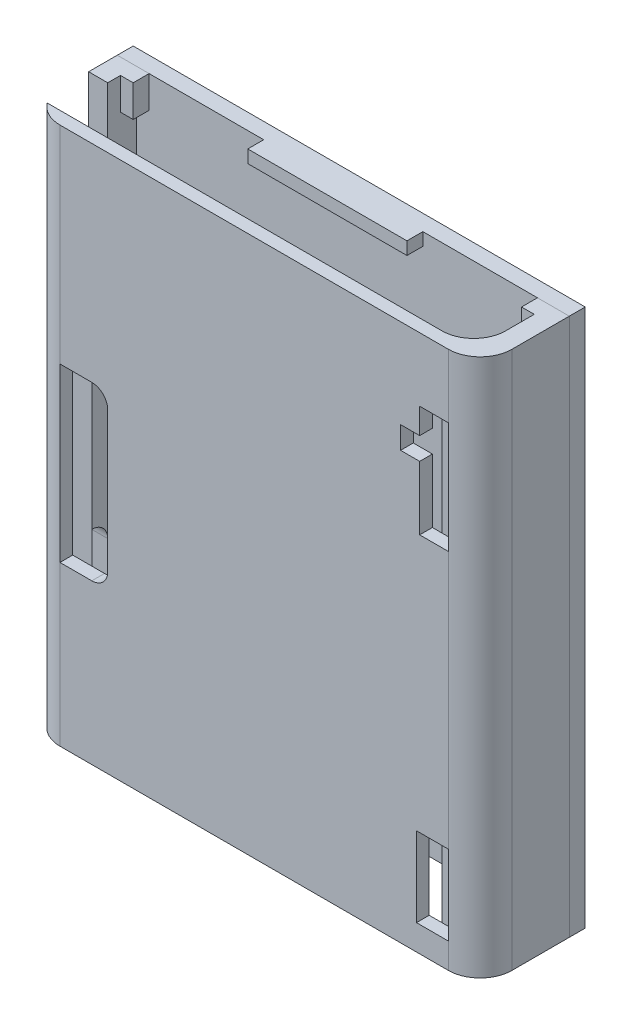
SolidWorks part; units mm, degrees
material "PEI"
ref_plane "前视基准面" through (0, 0, 0) normal (0, 0, 1) x (1, 0, 0)
ref_plane "上视基准面" through (0, 0, 0) normal (0, 1, 0) x (1, 0, 0)
ref_plane "右视基准面" through (0, 0, 0) normal (1, 0, 0) x (0, 0, -1)
other "Configuration Table"
sketch "草图2" plane through (0, 0, 0) normal (0, 0, 1) x (1, 0, 0)
  line L1 (-38.7902, 28.5822) -> (91.2098, 28.5822)
  line L2 (-38.7902, 28.5822) -> (-38.7902, -140.4178)
  line L3 (-38.7902, -140.4178) -> (91.2098, -140.4178)
  line L4 (91.2098, 28.5822) -> (91.2098, -140.4178)
  dimension "D1" = 130
  dimension "D2" = 169
extrude "凸台-拉伸1" add sketch "草图2" along normal blind 5
sketch "草图3" plane through (0, 0, 5) normal (0, 0, 1) x (1, 0, 0)
  line L0 (91.2098, 28.5822) -> (-38.7902, 28.5822) construction
  line L1 (1.2098, 24.5822) -> (51.2098, 24.5822)
  line L2 (-34.7902, -11.4178) -> (-34.7902, -100.4178)
  line L3 (1.2098, -136.4178) -> (51.2098, -136.4178)
  line L4 (87.2098, -11.4178) -> (87.2098, -100.4178)
  line L5 (-38.7902, -140.4178) -> (91.2098, -140.4178) construction
  line L6 (-38.7902, 28.5822) -> (-38.7902, -140.4178) construction
  line L7 (91.2098, -140.4178) -> (91.2098, 28.5822) construction
  line L8 (1.2098, 28.5822) -> (1.2098, 24.5822)
  line L9 (51.2098, -140.4178) -> (51.2098, -136.4178)
  line L10 (-38.7902, -11.4178) -> (-34.7902, -11.4178)
  line L11 (-38.7902, -100.4178) -> (-34.7902, -100.4178)
  line L12 (-38.7902, 28.5822) -> (-38.7902, -140.4178)
  line L13 (-38.7902, -140.4178) -> (91.2098, -140.4178)
  line L14 (91.2098, -140.4178) -> (91.2098, 28.5822)
  line L15 (91.2098, 28.5822) -> (-38.7902, 28.5822)
  line L16 (-38.7902, -11.4178) -> (-38.7902, -100.4178)
  line L17 (1.2098, -140.4178) -> (51.2098, -140.4178)
  line L18 (91.2098, -100.4178) -> (91.2098, -11.4178)
  line L19 (51.2098, 28.5822) -> (1.2098, 28.5822)
  line L20 (1.2098, -136.4178) -> (1.2098, -140.4178)
  line L21 (87.2098, -11.4178) -> (91.2098, -11.4178)
  line L22 (51.2098, 24.5822) -> (51.2098, 28.5822)
  line L23 (87.2098, -100.4178) -> (91.2098, -100.4178)
  dimension "D1" = 4
  dimension "D2" = 4
  dimension "D3" = 4
  dimension "D4" = 4
  dimension "D6" = 40
  dimension "D7" = 40
  dimension "D8" = 40
  dimension "D9" = 40
  dimension "D5" = 0
extrude "凸台-拉伸2" add sketch "草图3" along normal blind 5
sketch "草图4" plane through (0, -11.4178, 0) normal (0, 1, 0) x (1, 0, 0)
  line L0 (91.2098, -10) -> (91.2098, -12)
  line L1 (91.2098, -12) -> (86.2098, -12)
  line L2 (86.2098, -12) -> (85.2098, -10)
  line L3 (85.2098, -10) -> (87.2098, -10)
  line L4 (87.2098, -10) -> (87.2098, -5) construction
  line L5 (91.2098, -10) -> (87.2098, -10) construction
  line M6 (87.2098, -10) -> (91.2098, -10)
  dimension "D1" = 2
  dimension "D2" = 2
  dimension "D3" = 5
extrude "凸台-拉伸3" add sketch "草图4" against normal up to surface (89 mm away) contours L3 L2 L1 L0 M6 up to face at (89.2098, -100.4178, 7.5)
sketch "草图5" plane through (0, 0, 5) normal (0, 0, 1) x (1, 0, 0)
  line L0 (-38.7902, -140.4178) -> (1.2098, -140.4178) construction
  line L1 (-38.7902, 28.5822) -> (-44.7902, 28.5822)
  line L2 (-38.7902, 28.5822) -> (-38.7902, -140.4178)
  line L3 (-38.7902, -140.4178) -> (-44.7902, -140.4178)
  line L4 (-44.7902, 28.5822) -> (-44.7902, -140.4178)
  line L5 (91.2098, 28.5822) -> (97.2098, 28.5822)
  line L6 (91.2098, 28.5822) -> (91.2098, -140.4178)
  line L7 (91.2098, -140.4178) -> (97.2098, -140.4178)
  line L8 (97.2098, 28.5822) -> (97.2098, -140.4178)
  line L9 (51.2098, -140.4178) -> (91.2098, -140.4178) construction
  dimension "D1" = 6
  dimension "D2" = 6
extrude "凸台-拉伸4" add sketch "草图5" against normal up to surface (5 mm away) up to face at (26.2098, -55.9178, 0)
sketch "草图6" plane through (0, 28.5822, 0) normal (0, 1, 0) x (1, 0, 0)
  line L0 (-38.7902, -10) -> (-38.7902, -5) construction
  line L1 (-44.7902, -5) -> (-38.7902, -5)
  line L2 (-44.7902, -5) -> (-44.7902, -23)
  line L4 (-38.7902, -5) -> (-38.7902, -19)
  line L5 (-34.7902, -33) -> (87.2098, -33)
  line L6 (-38.7902, -33) -> (-38.7902, -32.1652)
  line L7 (-28.7902, -29) -> (81.2098, -29)
  line L10 (97.2098, -23) -> (97.2098, -5)
  line L11 (97.2098, -5) -> (91.2098, -5)
  line L12 (91.2098, -19) -> (91.2098, -5)
  line L13 (97.2098, 0) -> (97.2098, -5) construction
  line L14 (1.2098, -5) -> (-44.7902, -5) construction
  arc A0 (97.2098, -23) -> (87.2098, -33) centre (87.2098, -23) cw
  arc A1 (81.2098, -29) -> (91.2098, -19) centre (81.2098, -19) ccw
  arc A2 (-34.7902, -33) -> (-44.7902, -23) centre (-34.7902, -23) cw
  arc A3 (-28.7902, -29) -> (-38.7902, -19) centre (-28.7902, -19) cw
  line M7 (-44.7902, -5) -> (1.2098, -5)
  line M11 (51.2098, -5) -> (97.2098, -5)
  dimension "D3" = 10
  dimension "D1" = 24
  dimension "D2" = 4
extrude "凸台-拉伸5" add sketch "草图6" against normal up to surface (169 mm away) separate body contours L7 A3 L4 L2 A2 L5 A0 L10 L12 A1 M7 M11 up to face at (26.2098, -140.4178, 5)
sketch "草图7" plane through (0, 0, 5) normal (0, 0, 1) x (1, 0, 0)
  line L0 (-34.7902, -100.4178) -> (-34.7902, -11.4178) construction
  line L1 (91.2098, -140.4178) -> (87.2098, -140.4178)
  line L2 (91.2098, -140.4178) -> (91.2098, -130.4178)
  line L3 (91.2098, -130.4178) -> (87.2098, -130.4178)
  line L4 (87.2098, -140.4178) -> (87.2098, -130.4178)
  line L5 (-38.7902, -140.4178) -> (-34.7902, -140.4178)
  line L6 (-38.7902, -140.4178) -> (-38.7902, -130.4178)
  line L7 (-38.7902, -130.4178) -> (-34.7902, -130.4178)
  line L8 (-34.7902, -140.4178) -> (-34.7902, -130.4178)
  line L9 (91.2098, 28.5822) -> (87.2098, 28.5822)
  line L10 (91.2098, 28.5822) -> (91.2098, 18.5822)
  line L11 (91.2098, 18.5822) -> (87.2098, 18.5822)
  line L12 (87.2098, 28.5822) -> (87.2098, 18.5822)
  line L13 (-38.7902, 28.5822) -> (-34.7902, 28.5822)
  line L14 (-38.7902, 28.5822) -> (-38.7902, 18.5822)
  line L15 (-38.7902, 18.5822) -> (-34.7902, 18.5822)
  line L16 (-34.7902, 28.5822) -> (-34.7902, 18.5822)
  line L17 (87.2098, -11.4178) -> (87.2098, -100.4178) construction
  line M6 (-44.7902, -140.4178) -> (1.2098, -140.4178)
  line M12 (97.2098, 28.5822) -> (51.2098, 28.5822)
  line M16 (1.2098, 28.5822) -> (-44.7902, 28.5822)
  dimension "D1" = 10
  dimension "D2" = 10
  dimension "D3" = 10
  dimension "D4" = 10
extrude "凸台-拉伸6" add sketch "草图7" along normal up to surface (5 mm away) contours L8 L7 L6 M6 | L16 L14 L15 M16 | L12 L11 L10 M12 | L4 L3 L2 L1 up to face at (-36.7902, -55.9178, 10)
sketch "草图8" plane through (0, 0, 0) normal (0, 0, -1) x (-1, 0, 0)
  line L1 (-97.2098, 28.5822) -> (-87.2098, 28.5822)
  line L2 (-97.2098, 28.5822) -> (-97.2098, 18.5822)
  line L3 (-97.2098, 18.5822) -> (-87.2098, 18.5822)
  line L4 (-87.2098, 28.5822) -> (-87.2098, 18.5822)
  line L5 (-97.2098, 28.5822) -> (-87.2098, 18.5822) construction
  line L6 (-97.2098, 18.5822) -> (-87.2098, 28.5822) construction
  line L7 (44.7902, 28.5822) -> (34.7902, 28.5822)
  line L8 (44.7902, 28.5822) -> (44.7902, 18.5822)
  line L9 (44.7902, 18.5822) -> (34.7902, 18.5822)
  line L10 (34.7902, 28.5822) -> (34.7902, 18.5822)
  line L11 (44.7902, 28.5822) -> (34.7902, 18.5822) construction
  line L12 (44.7902, 18.5822) -> (34.7902, 28.5822) construction
  line L13 (44.7902, -140.4178) -> (34.7902, -140.4178)
  line L14 (44.7902, -140.4178) -> (44.7902, -130.4178)
  line L15 (44.7902, -130.4178) -> (34.7902, -130.4178)
  line L16 (34.7902, -140.4178) -> (34.7902, -130.4178)
  line L17 (44.7902, -140.4178) -> (34.7902, -130.4178) construction
  line L18 (44.7902, -130.4178) -> (34.7902, -140.4178) construction
  line L19 (-97.2098, -140.4178) -> (-87.2098, -140.4178)
  line L20 (-97.2098, -140.4178) -> (-97.2098, -130.4178)
  line L21 (-97.2098, -130.4178) -> (-87.2098, -130.4178)
  line L22 (-87.2098, -140.4178) -> (-87.2098, -130.4178)
  line L23 (-97.2098, -140.4178) -> (-87.2098, -130.4178) construction
  line L24 (-97.2098, -130.4178) -> (-87.2098, -140.4178) construction
  circle A0 centre (-92.2098, 23.5822) radius 2.2
  circle A1 centre (39.7902, 23.5822) radius 2.2
  circle A2 centre (-92.2098, -135.4178) radius 2.2
  circle A3 centre (39.7902, -135.4178) radius 2.2
  point P4 (-92.2098, 23.5822)
  point P10 (39.7902, 23.5822)
  point P16 (39.7902, -135.4178)
  point P22 (-92.2098, -135.4178)
  dimension "D4" = 4.4
  dimension "D5" = 4.4
  dimension "D6" = 4.4
  dimension "D7" = 4.4
  dimension "D1" = 10
  dimension "D2" = 10
  dimension "D3" = 10
extrude "切除-拉伸1" cut sketch "草图8" against normal blind 9 contours A3 | A1 | A0 | A2
sketch "草图9" plane through (-44.7902, 0, 0) normal (-1, 0, 0) x (0, 0, 1)
  line L0 (29, -140.4178) -> (29, 28.5822) construction
  line L1 (14, -140.4178) -> (29, -140.4178)
  line L2 (14, -140.4178) -> (14, -95.4178)
  line L3 (19, -90.4178) -> (24, -90.4178)
  line L4 (29, -140.4178) -> (29, -95.4178)
  line L5 (14, -140.4178) -> (29, -90.4178) construction
  line L6 (14, -90.4178) -> (29, -140.4178) construction
  line L7 (29, -31.4178) -> (29, 28.5822)
  line L8 (23, -140.4178) -> (5, -140.4178) construction
  line L9 (5, 28.5822) -> (23, 28.5822) construction
  line L10 (14, 28.5822) -> (29, 28.5822)
  line L11 (14, 28.5822) -> (14, -31.4178)
  line L12 (19, -36.4178) -> (24, -36.4178)
  line L13 (29, 28.5822) -> (29, -36.4178)
  line L14 (14, 28.5822) -> (29, -36.4178) construction
  line L15 (14, -36.4178) -> (29, 28.5822) construction
  arc A0 (29, -95.4178) -> (24, -90.4178) centre (24, -95.4178) ccw
  arc A1 (14, -95.4178) -> (19, -90.4178) centre (19, -95.4178) cw
  arc A2 (29, -31.4178) -> (24, -36.4178) centre (24, -31.4178) cw
  arc A3 (14, -31.4178) -> (19, -36.4178) centre (19, -31.4178) ccw
  point P4 (21.5, -115.4178)
  point P19 (21.5, -3.9178)
  line M6 (5, -140.4178) -> (23, -140.4178)
  line M7 (23, -140.4178) -> (23, 28.5822)
  line M8 (23, 28.5822) -> (5, 28.5822)
  dimension "D3" = 5
  dimension "D5" = 5
  dimension "D1" = 50
  dimension "D2" = 15
  dimension "D4" = 65
extrude "切除-拉伸2" cut sketch "草图9" against normal up to next contours A1 L2 L3 M6 M7 | L4 A0 L3 L1 M7 | A2 L7 L10 L12 M7 | L11 A3 L12 M7 M8
sketch "草图10" plane through (0, 0, 33) normal (0, 0, 1) x (1, 0, 0)
  line L0 (-34.7902, -100.4178) -> (-34.7902, -11.4178) construction
  line L1 (-34.7902, -100.4178) -> (-34.7902, -11.4178)
  line L2 (87.2098, -140.4178) -> (-34.7902, -140.4178) construction
  line L3 (-34.7902, -36.4178) -> (-24.7902, -36.4178)
  line L4 (-34.7902, -36.4178) -> (-34.7902, -90.4178)
  line L5 (-34.7902, -90.4178) -> (-24.7902, -90.4178)
  line L6 (-19.7902, -41.4178) -> (-19.7902, -85.4178)
  line L7 (-34.7902, -36.4178) -> (-19.7902, -90.4178) construction
  line L8 (-34.7902, -90.4178) -> (-19.7902, -36.4178) construction
  line L9 (-34.7902, 28.5822) -> (87.2098, 28.5822) construction
  line L10 (87.2098, -11.4178) -> (87.2098, -100.4178) construction
  line L11 (87.2098, -11.4178) -> (87.2098, -100.4178)
  line L12 (78.2098, 8.5822) -> (78.2098, 0.5822)
  line L13 (78.2098, 8.5822) -> (87.2098, 8.5822)
  line L14 (72.2098, 0.5822) -> (72.2098, -6.4178)
  line L15 (78.2098, -26.4178) -> (87.2098, -26.4178)
  line L16 (87.2098, 8.5822) -> (87.2098, -26.4178)
  line L17 (75.6384, 0.5822) -> (87.2098, -26.4178) construction
  line L18 (78.2098, -12.4178) -> (87.2098, 8.5822) construction
  line L19 (77.2098, -107.4178) -> (87.2098, -107.4178)
  line L20 (77.2098, -107.4178) -> (77.2098, -132.4178)
  line L21 (77.2098, -132.4178) -> (87.2098, -132.4178)
  line L22 (87.2098, -107.4178) -> (87.2098, -132.4178)
  line L23 (77.2098, -107.4178) -> (87.2098, -132.4178) construction
  line L24 (77.2098, -132.4178) -> (87.2098, -107.4178) construction
  line L25 (78.2098, 0.5822) -> (72.2098, 0.5822)
  line L26 (72.2098, 0.5822) -> (72.2098, -6.4178)
  line L27 (72.2098, -6.4178) -> (78.2098, -6.4178)
  line L28 (78.2098, -6.4178) -> (78.2098, -26.4178)
  arc A0 (-24.7902, -90.4178) -> (-19.7902, -85.4178) centre (-24.7902, -85.4178) ccw
  arc A1 (-19.7902, -41.4178) -> (-24.7902, -36.4178) centre (-24.7902, -41.4178) ccw
  point P6 (-27.2902, -63.4178)
  point P23 (79.7098, -8.9178)
  point P28 (82.2098, -119.9178)
  line M7 (87.2098, -140.4178) -> (87.2098, 28.5822)
  dimension "D4" = 5
  dimension "D1" = 50
  dimension "D2" = 65
  dimension "D3" = 15
  dimension "D5" = 8
  dimension "D6" = 25
  dimension "D7" = 10
  dimension "D8" = 20
  dimension "D9" = 35
  dimension "D10" = 15
  dimension "D11" = 9
  dimension "D12" = 8
  dimension "D13" = 7
extrude "切除-拉伸3" cut sketch "草图10" against normal up to surface (4 mm away) contours L6 A1 L3 L1 L5 A0 | L27 L28 L15 L11 L13 L12 L25 L14 M7 | L20 L21 L19 M7 up to face at (-8.2902, -59.6678, 29)
